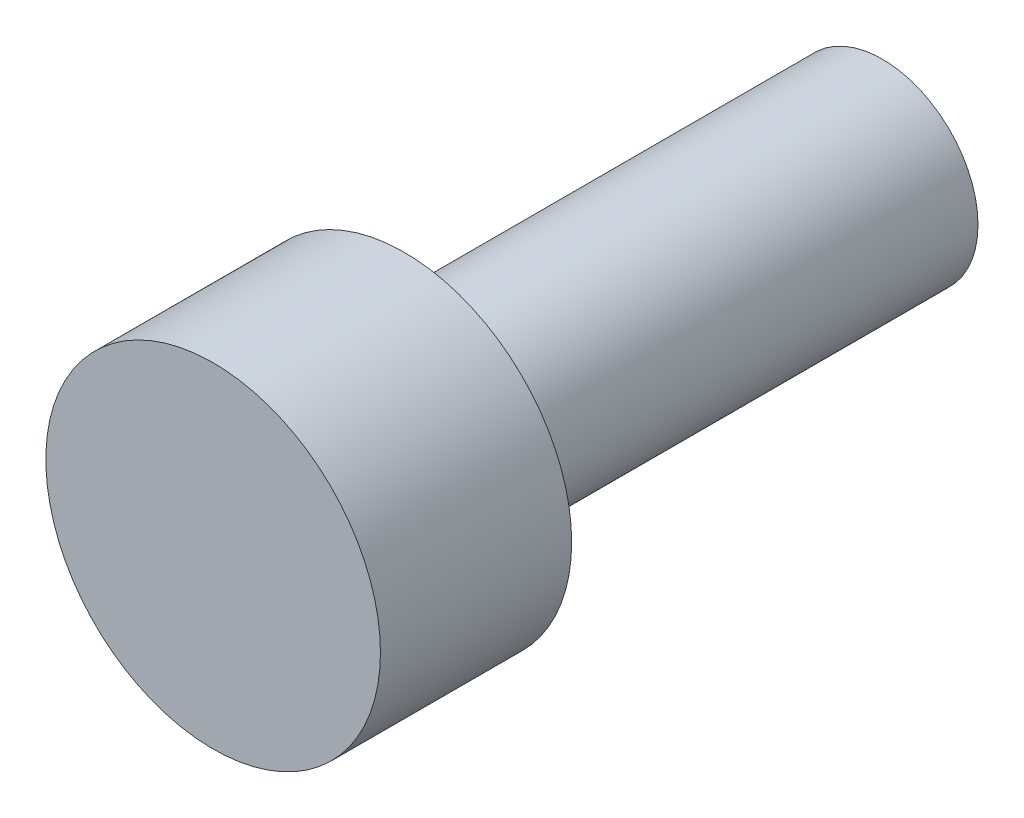
SolidWorks part; units mm, degrees
ref_plane "前视基准面" through (0, 0, 0) normal (0, 0, 1) x (1, 0, 0)
ref_plane "上视基准面" through (0, 0, 0) normal (0, 1, 0) x (1, 0, 0)
ref_plane "右视基准面" through (0, 0, 0) normal (1, 0, 0) x (0, 0, -1)
other "Configuration Table"
sketch "Sketch_Nominal_shank" plane through (0, 0, 0) normal (0, 0, 1) x (1, 0, 0)
  circle A0 centre (0, 0) radius 2
  dimension "D1" = 4
extrude "Nominal_shank" add sketch "Sketch_Nominal_shank" along normal blind 10 from offset 10
sketch "Sketch_Head" plane through (0, 0, 0) normal (0, 0, 1) x (1, 0, 0)
  circle A0 centre (0, 0) radius 3.5
  dimension "D1" = 7
extrude "Head" add sketch "Sketch_Head" along normal blind 4 from offset 0
